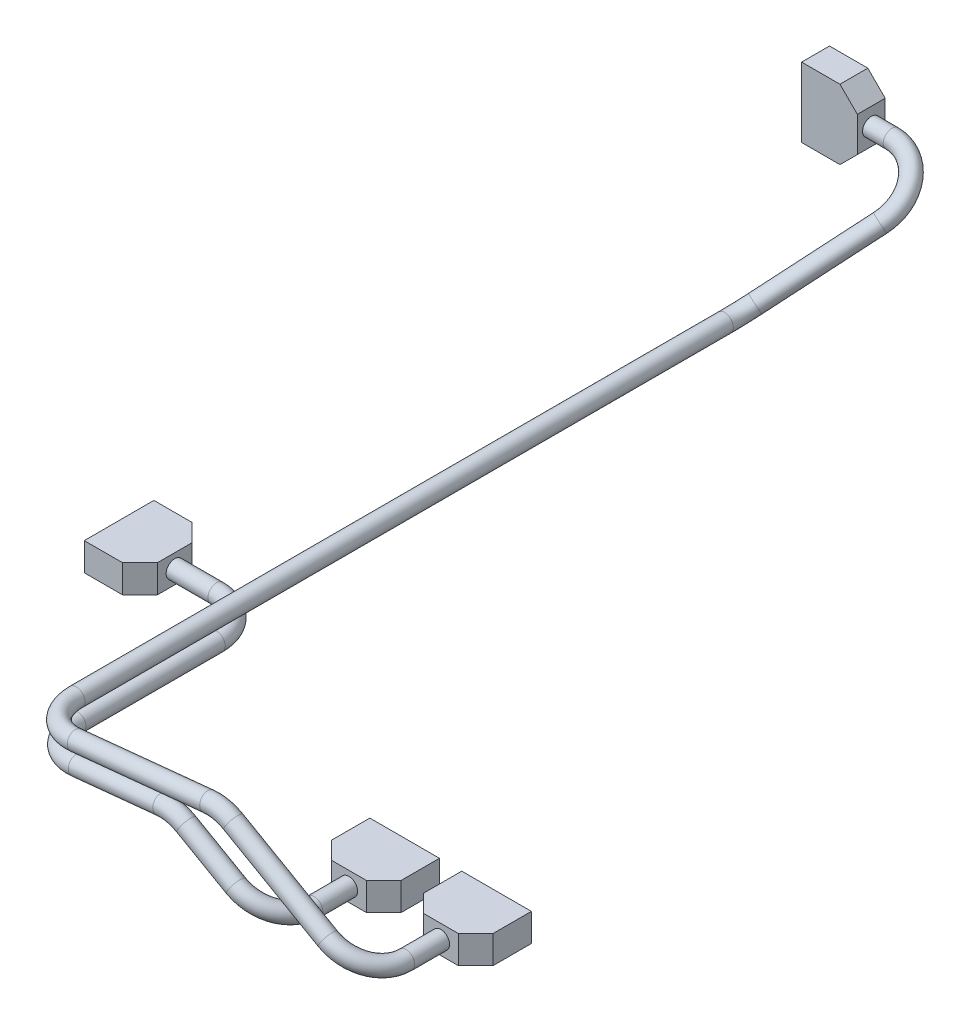
SolidWorks part; units mm, degrees
material "ASTM A36 Steel"
ref_plane "Front Plane" through (0, 0, 0) normal (0, 0, 1) x (1, 0, 0)
ref_plane "Top Plane" through (0, 0, 0) normal (0, 1, 0) x (1, 0, 0)
ref_plane "Right Plane" through (0, 0, 0) normal (1, 0, 0) x (0, 0, -1)
ref_plane "Plane1" through (0, -203.2, 0) normal (0, 1, 0) x (-1, 0, 0)
ref_plane "Plane2" through (0, -222.25, 0) normal (0, 1, 0) x (-1, 0, 0)
ref_plane "Plane5" through (0, -193.675, 0) normal (0, 1, 0) x (-1, 0, 0)
sketch "Sketch1" plane through (0, -203.2, 0) normal (0, 1, 0) x (-1, 0, 0)
  line L0 (-19.05, -212.725) -> (-19.05, -244.475)
  line L1 (-19.05, -244.475) -> (-36.5252, -244.475)
  line L2 (-36.5252, -244.475) -> (-44.45, -236.5502)
  line L3 (-44.45, -236.5502) -> (-44.45, -220.6498)
  line L4 (-36.5252, -212.725) -> (-44.45, -220.6498)
  line L5 (-19.05, -212.725) -> (-36.5252, -212.725)
  line L6 (-82.55, -228.6) -> (-44.45, -228.6) construction
  line L8 (-82.55, -228.6) -> (-82.55, -127) construction
  dimension "D1" = 45
  dimension "D2" = 31.75
  dimension "D3" = 7.9248
  dimension "D4" = 25.4
  dimension "D5" = 19.05
  dimension "D6" = 228.6
  dimension "D7" = 38.1
  dimension "D8" = 127
extrude "Boss-Extrude1" add sketch "Sketch1" along normal mid plane 12.7
sketch "Sketch2" plane through (0, -222.25, 0) normal (0, 1, 0) x (-1, 0, 0)
  line L0 (-174.625, -187.325) -> (-206.375, -187.325)
  line L1 (-206.375, -187.325) -> (-206.375, -169.8498)
  line L2 (-206.375, -169.8498) -> (-198.4502, -161.925)
  line L3 (-198.4502, -161.925) -> (-182.5498, -161.925)
  line L4 (-190.5, -127) -> (-190.5, -161.925) construction
  line L5 (-174.625, -169.8498) -> (-182.5498, -161.925)
  line L6 (-174.625, -187.325) -> (-174.625, -169.8498)
  dimension "D1" = 45
  dimension "D2" = 25.4
  dimension "D3" = 31.75
  dimension "D4" = 7.9248
  dimension "D5" = 187.325
  dimension "D6" = 190.5
extrude "Boss-Extrude2" add sketch "Sketch2" along normal mid plane 12.7 separate body
ref_plane "Plane3" through (0, 0, -127) normal (0, 0, 1) x (1, 0, 0)
sketch "Sketch3" plane through (0, 0, -127) normal (0, 0, 1) x (1, 0, 0)
  line L0 (82.55, -203.2) -> (146.05, -196.85) construction
  line L1 (146.05, -196.85) -> (190.5, -222.25) construction
  dimension "D1" = 63.5
  dimension "D2" = 6.35
sketch3d "3DSketch1"
  line L0 (44.45, -203.2, -228.6) -> (63.5, -203.2, -228.6)
  line L1 (82.55, -203.2, -209.55) -> (82.55, -203.2, -146.05)
  line L2 (101.5055, -201.3045, -127) -> (139.9904, -197.456, -127)
  line L3 (151.3374, -199.8714, -127) -> (173.96, -212.7986, -127)
  line L4 (190.5, -222.25, -146.05) -> (190.5, -222.25, -161.925)
  arc A0 (173.96, -212.7986, -127) -> (190.5, -222.25, -146.05) centre (173.96, -212.7986, -146.05) ccw
  arc A1 (139.9904, -197.456, -127) -> (151.3374, -199.8714, -127) centre (141.886, -216.4114, -127) ccw
  arc A2 (82.55, -203.2, -146.05) -> (101.5055, -201.3045, -127) centre (101.5055, -201.3045, -146.05) ccw
  arc A3 (63.5, -203.2, -228.6) -> (82.55, -203.2, -209.55) centre (63.5, -203.2, -209.55) ccw
  point P14 (190.5, -222.25, -127)
  point P15 (183.4114, -196.2585, -146.05)
  point P18 (146.05, -196.85, -127)
  point P19 (141.886, -216.4114, -146.05)
  point P22 (82.55, -203.2, -127)
  point P23 (99.6099, -182.349, -146.05)
  point P26 (82.55, -203.2, -228.6)
  point P27 (63.5, -222.25, -209.55)
  dimension "D1" = 19.05
sketch "Sketch4" plane through (44.45, 0, 0) normal (1, 0, 0) x (0, 0, -1)
  circle A0 centre (228.6, -203.2) radius 3.9751
  dimension "D1" = 7.9502
sweep "Sweep1" add profiles "Sketch4" path "3DSketch1"
ref_plane "Plane4" through (0, 0, -514.35) normal (0, 0, 1) x (1, 0, 0)
sketch "Sketch5" plane through (0, 0, -514.35) normal (0, 0, 1) x (1, 0, 0)
  line L0 (50.8, -139.7) -> (50.8, -171.45)
  line L1 (50.8, -139.7) -> (68.2752, -139.7)
  line L2 (68.2752, -139.7) -> (76.2, -147.6248)
  line L3 (76.2, -147.6248) -> (76.2, -163.5252)
  line L4 (76.2, -155.575) -> (114.3, -155.575) construction
  line L5 (50.8, -171.45) -> (68.2752, -171.45)
  line L6 (68.2752, -171.45) -> (76.2, -163.5252)
  dimension "D1" = 45
  dimension "D2" = 7.9248
  dimension "D3" = 25.4
  dimension "D4" = 31.75
  dimension "D5" = 38.1
  dimension "D6" = 155.575
  dimension "D7" = 50.8
extrude "Boss-Extrude3" add sketch "Sketch5" along normal mid plane 12.7 separate body
sketch "Sketch6" plane through (0, -222.25, 0) normal (0, 1, 0) x (-1, 0, 0)
  line L0 (-216.535, -187.325) -> (-248.285, -187.325)
  line L1 (-248.285, -187.325) -> (-248.285, -169.8498)
  line L2 (-248.285, -169.8498) -> (-240.3602, -161.925)
  line L3 (-240.3602, -161.925) -> (-224.4598, -161.925)
  line L4 (-232.41, -161.925) -> (-232.41, -127) construction
  line L5 (-206.375, -187.325) -> (-206.375, -169.8498) construction
  line L6 (-206.375, -169.8498) -> (-198.4502, -161.925) construction
  line L7 (-216.535, -187.325) -> (-216.535, -169.8498)
  line L8 (-216.535, -169.8498) -> (-224.4598, -161.925)
  line L9 (-174.625, -187.325) -> (-206.375, -187.325) construction
  line L10 (-190.5, -127) -> (-190.5, -161.925) construction
  dimension "D2" = 41.91
extrude "Boss-Extrude4" add sketch "Sketch6" along normal mid plane 12.7 separate body
sketch "Sketch7" plane through (0, 0, -127) normal (0, 0, 1) x (1, 0, 0)
  line L0 (232.41, -222.25) -> (167.4612, -185.1364) construction
  line L1 (167.4612, -185.1364) -> (82.0749, -193.675) construction
  line L2 (146.05, -196.85) -> (190.5, -222.25) construction
  line L3 (82.55, -203.2) -> (146.05, -196.85) construction
  line L4 (26.8174, -193.675) -> (-26.8174, -193.675) construction
  dimension "D1" = 9.525
sketch "Sketch8" plane through (0, -193.675, 0) normal (0, 1, 0) x (-1, 0, 0)
  line L0 (-82.0749, -127) -> (-82.0749, -447.9954) construction
sketch3d "3DSketch2"
  line L0 (76.2, -155.575, -514.35) -> (85.6063, -155.575, -514.35)
  line L1 (103.1628, -168.7426, -491.4174) -> (84.545, -190.7547, -453.0815)
  line L2 (82.0749, -193.675, -441.6317) -> (82.0749, -193.675, -146.05)
  line L3 (101.0304, -191.7795, -127) -> (161.4016, -185.7423, -127)
  line L4 (172.7486, -188.1578, -127) -> (215.87, -212.7986, -127)
  line L5 (232.41, -222.25, -146.05) -> (232.41, -222.25, -161.925)
  arc A0 (84.545, -190.7547, -453.0815) -> (82.0749, -193.675, -441.6317) centre (94.3772, -179.13, -441.6317) ccw
  arc A1 (82.0749, -193.675, -146.05) -> (101.0304, -191.7795, -127) centre (101.0304, -191.7795, -146.05) ccw
  arc A2 (161.4016, -185.7423, -127) -> (172.7486, -188.1578, -127) centre (163.2971, -204.6978, -127) ccw
  arc A3 (215.87, -212.7986, -127) -> (232.41, -222.25, -146.05) centre (215.87, -212.7986, -146.05) ccw
  arc A4 (85.6063, -155.575, -514.35) -> (103.1628, -168.7426, -491.4174) centre (85.6063, -165.0608, -497.8296) ccw
  point P16 (82.0749, -193.675, -447.9954)
  point P17 (79.8321, -166.8278, -441.6317)
  point P20 (82.0749, -193.675, -127)
  point P21 (99.1348, -172.824, -146.05)
  point P24 (167.4612, -185.1364, -127)
  point P25 (163.2971, -204.6978, -146.05)
  point P28 (232.41, -222.25, -127)
  point P29 (225.3214, -196.2585, -146.05)
  point P32 (114.3, -155.575, -514.35)
  point P33 (85.6063, -181.5812, -507.3154)
  dimension "D1" = 19.05
  dimension "D2" = 19.05
sketch "Sketch9" plane through (76.2, 0, 0) normal (1, 0, 0) x (0, 0, -1)
  circle A0 centre (514.35, -155.575) radius 3.9751
  dimension "D1" = 7.9502
sweep "Sweep2" add profiles "Sketch9" path "3DSketch2"
